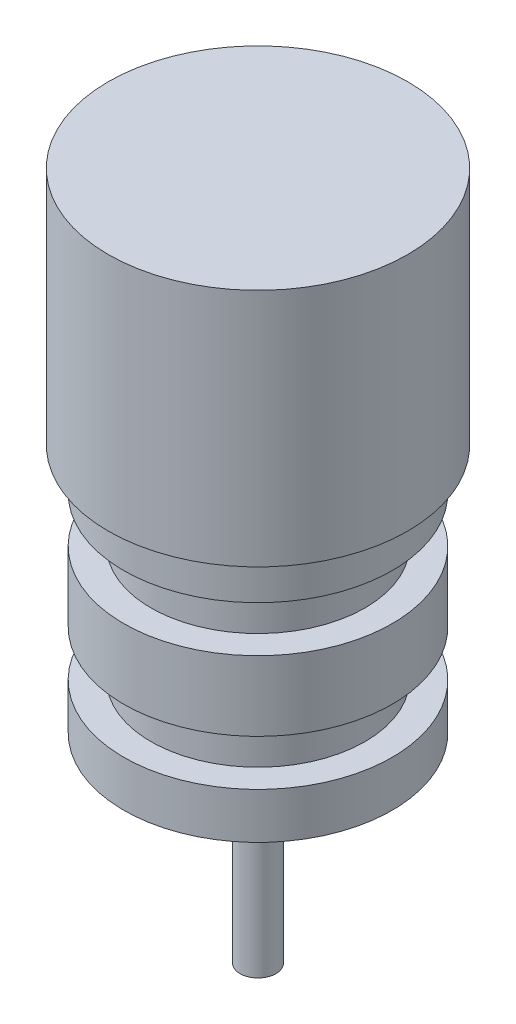
SolidWorks part; units mm, degrees
ref_plane "Plan de face" through (0, 0, 0) normal (0, 0, 1) x (1, 0, 0)
ref_plane "Plan de dessus" through (0, 0, 0) normal (0, 1, 0) x (1, 0, 0)
ref_plane "Plan de droite" through (0, 0, 0) normal (1, 0, 0) x (0, 0, -1)
sketch "Esquisse3" plane through (0, 0, 0) normal (0, 0, 1) x (1, 0, 0)
  line L0 (0, 0) -> (0, 83.371) construction
  line L1 (0, -20) -> (1.8, -20)
  line L2 (1.8, -20) -> (1.8, 0)
  line L3 (1.8, 0) -> (13.45, 0)
  line L4 (13.45, 0) -> (13.45, 4.6)
  line L5 (13.45, 4.6) -> (13.45, 9.2) construction
  line L6 (13.45, 9.2) -> (13.45, 16.2)
  line L7 (13.45, 16.2) -> (13.45, 20.8) construction
  line L8 (13.45, 20.8) -> (13.45, 25)
  line L9 (13.45, 25) -> (15, 25)
  line L10 (15, 25) -> (15, 49)
  line L11 (15, 49) -> (0, 49)
  line L12 (0, 49) -> (0, 0)
  line L13 (0, 0) -> (0, -20)
  line L14 (11.4879, 19.7) -> (11.4879, 5.7) construction
  line L15 (13.45, 20.8) -> (10.73, 20.8)
  line L16 (10.73, 20.8) -> (10.73, 16.2)
  line L17 (10.73, 16.2) -> (13.45, 16.2)
  line L18 (13.45, 9.2) -> (10.73, 9.2)
  line L19 (10.73, 9.2) -> (10.73, 4.6)
  line L20 (10.73, 4.6) -> (13.45, 4.6)
  arc A0 (13.45, 4.6) -> (13.45, 9.2) centre (13.45, 6.9) cw construction
  arc A1 (13.45, 16.2) -> (13.45, 20.8) centre (13.45, 18.5) cw construction
  dimension "D1" = 25
  dimension "D12" = 10.73
  dimension "D2" = 24
  dimension "D3" = 15
  dimension "D4" = 13.45
  dimension "D5" = 4.6
  dimension "D6" = 7
  dimension "D7" = 4.2
  dimension "D8" = 1.8
  dimension "D9" = 20
  dimension "D10" = 14
  dimension "D11" = 11.4879
revolve "Révolution1" add sketch "Esquisse3" angle 360 about L12
